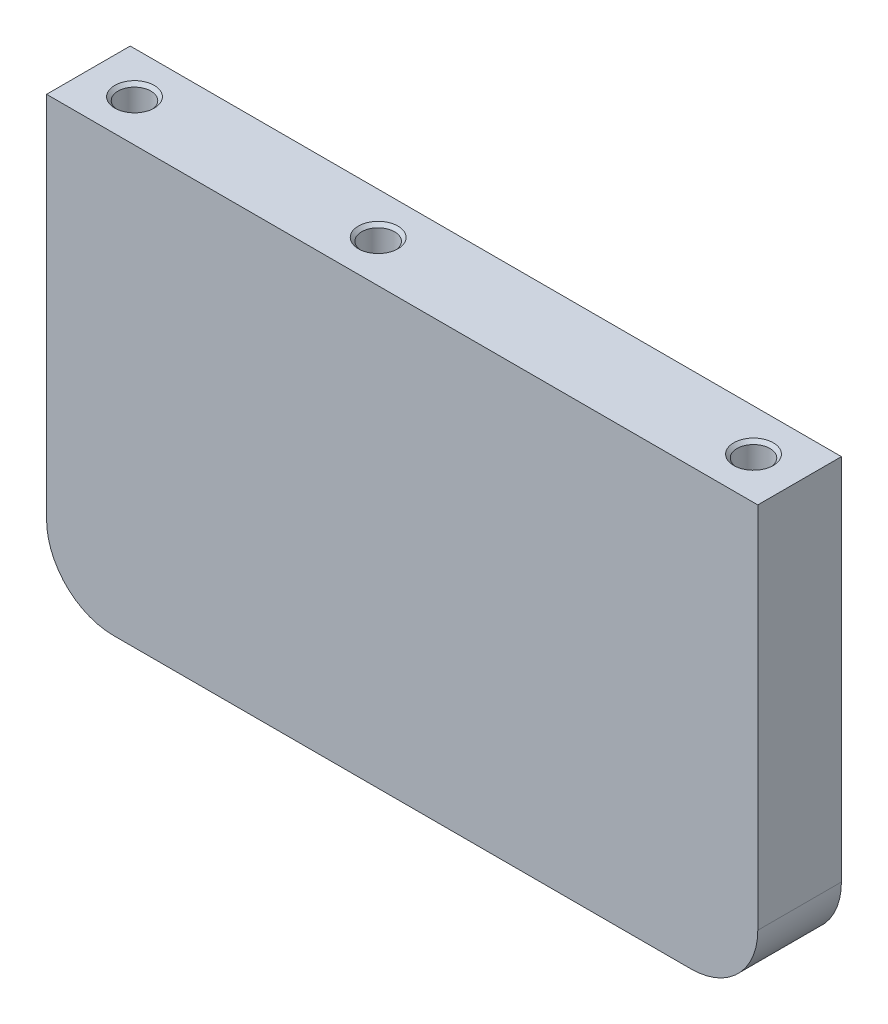
SolidWorks part; units mm, degrees
ref_plane "Front Plane" through (0, 0, 0) normal (0, 0, 1) x (1, 0, 0)
ref_plane "Top Plane" through (0, 0, 0) normal (0, 1, 0) x (1, 0, 0)
ref_plane "Right Plane" through (0, 0, 0) normal (1, 0, 0) x (0, 0, -1)
sketch "Sketch1" plane through (0, 0, 0) normal (0, 0, 1) x (1, 0, 0)
  line L10 (-36, 19.05) -> (18, 19.05)
  line L11 (-36, 19.05) -> (-36, -14)
  line L12 (-36, -14) -> (18, -14)
  line L13 (18, 19.05) -> (18, -14)
  circle A2 centre (0, 0) radius 11.05 construction
  circle A3 centre (-25, 0) radius 3.35 construction
  dimension "D2" = 6.7
  dimension "D5" = 19.05
  dimension "D6" = 11
  dimension "D3" = 25
  dimension "D1" = 22.1
  dimension "D8" = 54
  dimension "D4" = 14
  dimension "D7" = 18
extrude "Boss-Extrude1" add sketch "Sketch1" against normal blind 6.35
sketch "Sketch8" plane through (0, 19.05, 0) normal (0, 1, 0) x (1, 0, 0)
  line L0 (-36, 3.175) -> (18, 3.175) construction
  line L1 (-36, 6.35) -> (-36, 0) construction
  line L2 (18, 6.35) -> (18, 0) construction
  circle A1 centre (-32.5, 3.175) radius 1.25
  circle A2 centre (-14, 3.175) radius 1.25
  circle A3 centre (14.5, 3.175) radius 1.25
  dimension "D1" = 2.5
  dimension "D2" = 3.5
  dimension "D3" = 3.5
  dimension "D4" = 14
extrude "Cut-Extrude4" cut sketch "Sketch8" against normal blind 15
fillet "Fillet3" radius 5.08 2 edges at (18, -14, -3.175) (-36, -14, -3.175)
sketch "Sketch10" plane through (0, 0, -6.35) normal (0, 0, -1) x (-1, 0, 0)
  circle A0 centre (25, 0) radius 3.35 construction
  circle A1 centre (0, 0) radius 11.05 construction
  circle A2 centre (25, 0) radius 3.35
  circle A3 centre (0, 0) radius 11.05
extrude "Cut-Extrude5" cut sketch "Sketch10" against normal offset from surface (4.7625 mm away) 1.5875 up to face at (-9, -1.6407, 0)
chamfer "Chamfer1" distance 0.25 angle 45 3 edges at (14.5, 19.05, -1.925) (-14, 19.05, -1.925) (-32.5, 19.05, -1.925)
